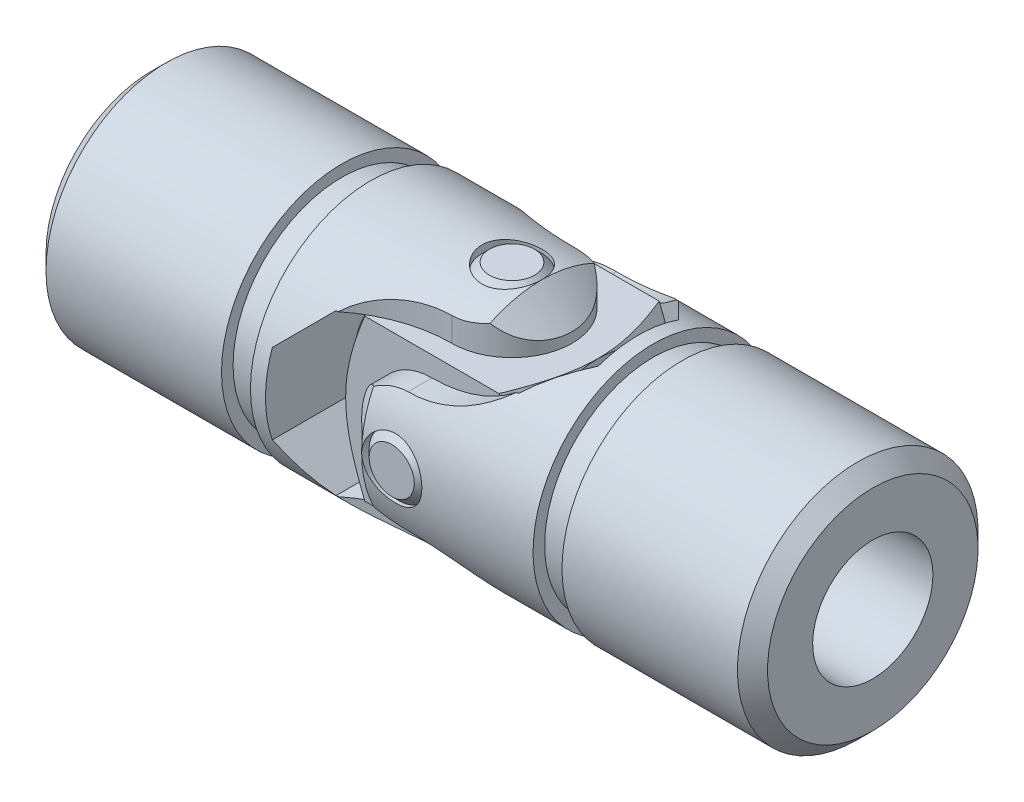
SolidWorks part; units mm, degrees
ref_plane "Front Plane" through (0, 0, 0) normal (0, 0, 1) x (1, 0, 0)
ref_plane "Top Plane" through (0, 0, 0) normal (0, 1, 0) x (1, 0, 0)
ref_plane "Right Plane" through (0, 0, 0) normal (1, 0, 0) x (0, 0, -1)
sketch "Sketch0" plane through (0, 0, 0) normal (0, 1, 0) x (1, 0, 0)
  line L0 (-47.625, 0) -> (47.625, 0) construction
  line L1 (-47.625, 15.875) -> (-47.625, -15.875) construction
  line L2 (-20.6375, 7.9375) -> (-20.6375, -7.9375) construction
  line L3 (-20.6375, 7.9375) -> (-12.7, 0) construction
  line L4 (-12.7, 0) -> (-20.6375, -7.9375) construction
  line L5 (-16.6688, 3.9688) -> (-16.6688, -3.9688) construction
  point P7 (-20.6375, 0)
  point P8 (0, 0)
  point P12 (-16.6688, 0)
sketch "Sketch1" plane through (0, 0, 0) normal (0, 1, 0) x (1, 0, 0)
  line L0 (-47.625, 15.875) -> (-22.473, 15.875)
  line L1 (7.9375, 15.875) -> (7.9375, 0)
  line L2 (7.9375, 0) -> (-47.625, 0)
  line L3 (-47.625, 0) -> (-47.625, 15.875)
  line L4 (-47.625, 15.875) -> (-47.625, -15.875) construction
  line L5 (-47.625, 0) -> (47.625, 0) construction
  line L6 (-18.6531, 15.875) -> (7.9375, 15.875)
  line L7 (-18.6531, 3.9688) -> (-18.6531, 14.347) construction
  line L8 (-22.473, 15.875) -> (-22.473, 14.347)
  line L9 (-22.473, 14.347) -> (-18.6531, 14.347)
  line L10 (-18.6531, 15.875) -> (-18.6531, 14.347)
  line L11 (0, 0) -> (15.875, 0) construction
  line L12 (-16.6688, 3.9688) -> (-20.6375, 3.9688) construction
  line L13 (-20.6375, 7.9375) -> (-20.6375, -7.9375) construction
  circle A0 centre (0, 0) radius 15.875 construction
  dimension "D1" = 3.8199
  dimension "D2" = 1.528
  dimension "D3" = 55.5625
revolve "Revolve1" add sketch "Sketch1" angle 360 about L0
chamfer "Chamfer1" distance 1.9844 angle 45 1 edges at (-47.625, 0, 15.875)
chamfer "Chamfer2" distance 3.9688 angle 45 1 edges at (7.9375, 0, 15.875)
sketch "Sketch2" plane through (0, 0, 0) normal (0, 1, 0) x (1, 0, 0)
  line L0 (-18.6531, 15.875) -> (-14.8332, 15.875) construction
  line L1 (-18.6531, 15.875) -> (7.9375, 15.875) construction
  line L2 (3.9687, 15.875) -> (-18.6531, 15.875) construction
  line L3 (-22.473, 14.347) -> (-18.6531, 14.347) construction
  line L4 (-47.625, 0) -> (7.9375, 0) construction
  line L5 (-14.8332, 15.875) -> (15.875, 15.875)
  line L6 (15.875, 15.875) -> (15.875, -15.875)
  line L7 (15.875, -15.875) -> (-14.8332, -15.875)
  line L8 (0, 7.9375) -> (0, 0) construction
  arc A0 (-14.8332, 15.875) -> (0, 7.9375) centre (0, 25.766) ccw
  arc A1 (0, -7.9375) -> (0, 7.9375) centre (0, 0) ccw
  arc A2 (-14.8332, -15.875) -> (0, -7.9375) centre (0, -25.766) cw
  dimension "D1" = 15.875
extrude "Extrude1" cut sketch "Sketch2" against normal through all and the other way through all
sketch "Sketch3" plane through (0, 0, 0) normal (0, 0, 1) x (1, 0, 0)
  line L0 (-11.3824, 10.5727) -> (-16.6688, 5.2864)
  line L1 (-11.3824, 10.5727) -> (15.875, 10.5728)
  line L2 (-16.6688, 5.2864) -> (-16.6688, -5.2864)
  line L3 (-11.3824, -10.5727) -> (15.875, -10.5728)
  line L4 (15.875, 10.5728) -> (15.875, -10.5728)
  line L5 (-16.6688, -5.2864) -> (-11.3824, -10.5727)
  dimension "D1" = 21.1455
  dimension "D2" = 5.2864
extrude "Extrude3" cut sketch "Sketch3" against normal through all and the other way through all
sketch "Sketch4" plane through (-47.625, 0, 0) normal (-1, 0, 0) x (0, 0, 1)
  circle A0 centre (0, 0) radius 7.9375
extrude "Extrude4" cut sketch "Sketch4" against normal up to vertex (26.9875 mm away) up to point (-20.6375, 0, -7.9375)
sketch "Sketch5" plane through (-20.6375, 0, 0) normal (-1, 0, 0) x (0, 0, 1)
  circle A0 centre (0, 0) radius 7.9375 construction
  circle A1 centre (0, 0) radius 7.9375
extrude "Extrude5" cut sketch "Sketch5" against normal through all draft 45
sketch "Sketch6" plane through (0, 0, 0) normal (0, 1, 0) x (1, 0, 0)
  line L0 (-47.625, 0) -> (47.625, 0) construction
  line L1 (7.9375, 0) -> (3.9687, 0) construction
  line L2 (3.9687, 0) -> (0, 0) construction
  circle A0 centre (0, 0) radius 3.9687
  arc A1 (0, -7.9375) -> (0, 7.9375) centre (0, 0) ccw construction
  dimension "D1" = 7.9375
extrude "Extrude6" cut sketch "Sketch6" against normal through all and the other way through all
mirror "Mirror1" about plane through (0, 0, 0) normal (1, 0, 0) of bodies 109 122
move or copy body "Body-Move/Copy1" bodies to move or copy 110 copy no rotation origin (0, 0, 0) rotation axis (1, 0, 0) rotation angle 90
sketch "Sketch18" plane through (0, 0, 0) normal (0, 1, 0) x (1, 0, 0)
  line L0 (-47.625, -7.9375) -> (-20.6375, -7.9375)
  line L3 (-47.625, 7.9375) -> (-20.6375, 7.9375)
  line L4 (-20.6375, 7.9375) -> (-20.6375, -7.9375)
  line L5 (20.6375, 7.9375) -> (20.6375, -7.9375)
  line L6 (20.6375, -7.9375) -> (47.625, -7.9375)
  line L7 (20.6375, 7.9375) -> (47.625, 7.9375)
  line L8 (0, 0) -> (20.6375, 0) construction
  line L9 (47.625, -13.8906) -> (47.625, 13.8906) construction
  line L11 (-20.6375, -7.9375) -> (-20.6375, 7.9375) construction
sketch "Sketch10" plane through (0, 0, 0) normal (0, 0, 1) x (1, 0, 0)
  line L0 (-11.3824, 10.5727) -> (11.3824, -10.5728) construction
  line L1 (-11.3824, 10.5727) -> (11.3824, 10.5727)
  line L2 (-11.3824, 10.5727) -> (-11.3824, -10.5728)
  line L3 (-11.3824, -10.5728) -> (11.3824, -10.5728)
  line L4 (11.3824, 10.5727) -> (11.3824, -10.5728)
  line L5 (0, 10.5727) -> (7.9375, 10.5727) construction
extrude "Extrude10" add sketch "Sketch10" against normal up to surface and the other way up to surface separate body up to face at (-3.9687, 0, -10.5727) other way up to face at (3.9688, 0, 10.5727)
sketch "Sketch11" plane through (11.3824, 0, 0) normal (1, 0, 0) x (0, 0, -1)
  line L4 (-10.5727, -10.5728) -> (-10.5728, 10.5727) construction
  circle A0 centre (0, 0) radius 10.5727
extrude "Extrude11" cut sketch "Sketch11" against normal through all draft 60 flip side to cut
sketch "Sketch12" plane through (-11.3824, -21.0185, 0) normal (1, 0, 0) x (0, -1, 0)
  circle A2 centre (-21.0185, 0) radius 10.5727
  circle A6 centre (-21.0185, 0) radius 10.5727
  dimension "D1" = 0
extrude "Extrude12" cut sketch "Sketch12" along normal through all draft 60 flip side to cut
sketch "Sketch13" plane through (0, 0, 0) normal (0, 1, 0) x (1, 0, 0)
  circle A0 centre (0, 0) radius 3.9687 construction
  circle A1 centre (0, 0) radius 3.9687
extrude "Extrude13" cut sketch "Sketch13" against normal through all and the other way through all
sketch "Sketch14" plane through (0, 0, 0) normal (0, 1, 0) x (1, 0, 0)
  circle A1 centre (0, 0) radius 3.9687
  circle A2 centre (0, 0) radius 3.9687
  dimension "D1" = 0
extrude "Extrude14" add sketch "Sketch14" along normal mid plane 31.75 separate body
sketch "Sketch15" plane through (0, 0, 0) normal (0, 0, 1) x (1, 0, 0)
  circle A0 centre (0, 0) radius 3.9687 construction
  circle A1 centre (0, 0) radius 3.9688
extrude "Extrude15" cut sketch "Sketch15" against normal through all and the other way through all
sketch "Sketch16" plane through (0, 0, 0) normal (0, 0, 1) x (1, 0, 0)
  circle A1 centre (0, 0) radius 3.9688
  circle A2 centre (0, 0) radius 3.9688
  dimension "D1" = 0
extrude "Extrude16" add sketch "Sketch16" along normal mid plane 31.75
chamfer "Chamfer3" distance 0.9922 angle 45 4 edges at (0, -15.875, 3.9687) (0, 15.875, 3.9687) (3.9688, 0, 15.875) (3.9688, 0, -15.875)
move or copy body "Body-Move/Copy2" [suppressed] bodies to move or copy 111 copy no rotation origin (0, 0, 0) rotation axis (0, 0, -1) rotation angle 25
equation "\"D2@Sketch3\" = \"D1@Sketch3\" / 4"
equation "\"D1@Extrude14\" = \"OD@Sketch0\""
equation "\"D1@Extrude16\" = \"D1@Extrude14\""
equation "\"D1@Sketch3\" = \"OD@Sketch0\"*.666"
equation "\"D2@Sketch3\" = \"D1@Sketch3\"/4"
equation "\"D1@Sketch1\" = \"D3@Sketch1\"*.06875"
equation "\"D2@Sketch1\" = \"D1@Sketch1\"/2.5"
equation "\"D1@Chamfer1\" = \"OD@Sketch0\"/16"
equation "\"D1@Chamfer2\" = \"D1@Chamfer1\"*2"
equation "\"D1@Chamfer3\" = \"D1@Chamfer1\"*.50"
